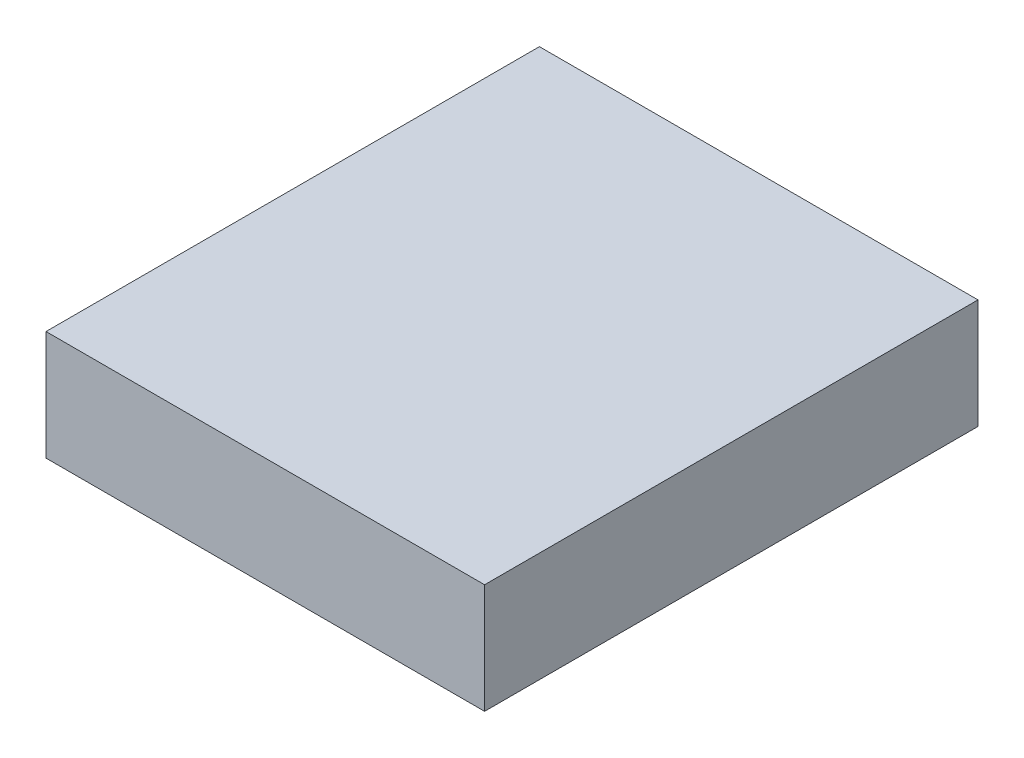
SolidWorks part; units mm, degrees
ref_plane "Front Plane" through (0, 0, 0) normal (0, 0, 1) x (1, 0, 0)
ref_plane "Top Plane" through (0, 0, 0) normal (0, 1, 0) x (1, 0, 0)
ref_plane "Right Plane" through (0, 0, 0) normal (1, 0, 0) x (0, 0, -1)
sketch "Sketch1" plane through (0, 0, 0) normal (0, 1, 0) x (1, 0, 0)
  line L1 (-1, -1.125) -> (1, -1.125)
  line L2 (-1, -1.125) -> (-1, 1.125)
  line L3 (-1, 1.125) -> (1, 1.125)
  line L4 (1, -1.125) -> (1, 1.125)
  line L5 (-1, -1.125) -> (1, 1.125) construction
  line L6 (-1, 1.125) -> (1, -1.125) construction
  point P0 (0, 0)
  dimension "D1" = 2.25
  dimension "D2" = 2
extrude "Boss-Extrude1" add sketch "Sketch1" along normal blind 0.5
